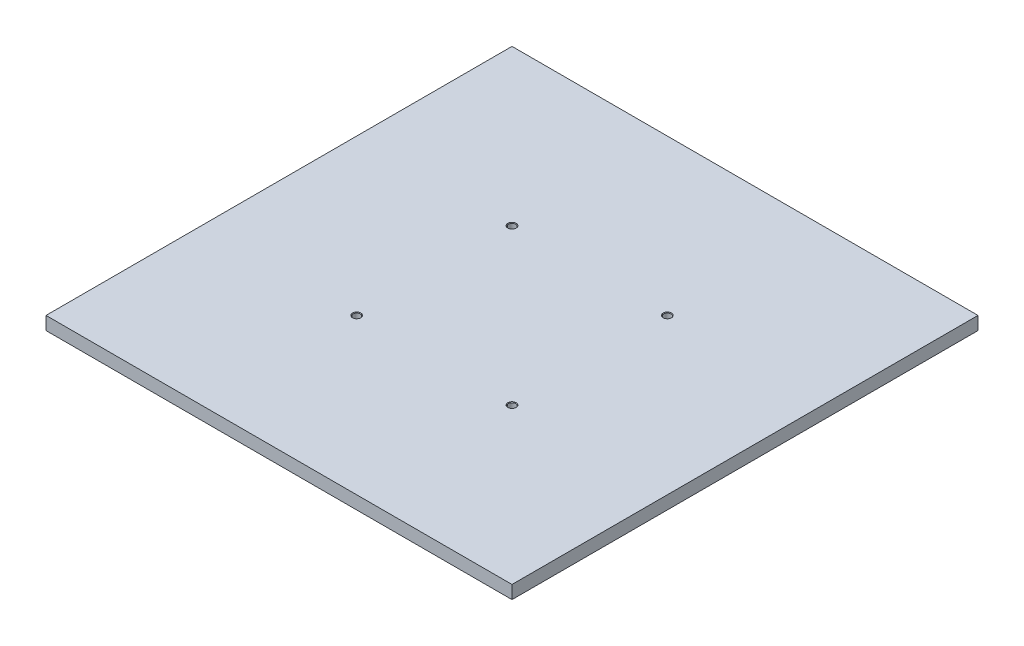
SolidWorks part; units mm, degrees
ref_plane "Front Plane" through (0, 0, 0) normal (0, 0, 1) x (1, 0, 0)
ref_plane "Top Plane" through (0, 0, 0) normal (0, 1, 0) x (1, 0, 0)
ref_plane "Right Plane" through (0, 0, 0) normal (1, 0, 0) x (0, 0, -1)
sketch "Esboço1" plane through (0, 0, 0) normal (0, 1, 0) x (1, 0, 0)
  line L1 (-225, -225) -> (225, -225)
  line L2 (-225, -225) -> (-225, 225)
  line L3 (-225, 225) -> (225, 225)
  line L4 (225, -225) -> (225, 225)
  line L5 (-225, -225) -> (225, 225) construction
  line L6 (-225, 225) -> (225, -225) construction
  point P0 (0, 0)
  dimension "D1" = 450
  dimension "D2" = 450
extrude "Ressalto-extrusão1" add sketch "Esboço1" along normal blind 12.7
sketch "Esboço2" plane through (0, 12.7, 0) normal (0, 1, 0) x (1, 0, 0)
  line L1 (-75, -75) -> (75, -75) construction
  line L2 (-75, -75) -> (-75, 75) construction
  line L3 (-75, 75) -> (75, 75) construction
  line L4 (75, -75) -> (75, 75) construction
  line L5 (-75, -75) -> (75, 75) construction
  line L6 (-75, 75) -> (75, -75) construction
  point P0 (0, 0)
  dimension "D1" = 150
  dimension "D2" = 150
hole_wizard "Furo roscado de M8x1.01" positions "Esboço3" profile "Esboço4" tap size "M8x1.0" standard "Ansi Metric" end condition through all
sketch "Esboço3" plane through (0, 12.7, 0) normal (0, 1, 0) x (1, 0, 0)
  point P0 (-75, 75)
  point P3 (75, 75)
  point P6 (75, -75)
  point P9 (-75, -75)
sketch "Esboço4" plane through (-75, 12.7, -75) normal (1, 0, 0) x (0, 0, 1)
  line L0 (0, 0) -> (0, 12.7)
  line L1 (0, 12.7) -> (3.5, 12.7)
  line L2 (3.5, 12.7) -> (3.5, 0.525)
  line L3 (3.5, 0.525) -> (4.025, 0)
  line L5 (4.025, 0) -> (0, 0)
  line L6 (-3.5, 0.525) -> (-4.025, 0) construction
  line L11 (0, -6.35) -> (0, 107.95) construction
  dimension "Thru Tap Drill Dia." = 7
  dimension "Thru Tap Drill Depth" = 12.7
  dimension "Near C'Sink Dia." = 8.05
  dimension "Near C'Sink Angle" = 90
cosmetic thread "Rosca de furo1"
cosmetic thread "Rosca de furo2"
cosmetic thread "Rosca de furo3"
cosmetic thread "Rosca de furo4"
